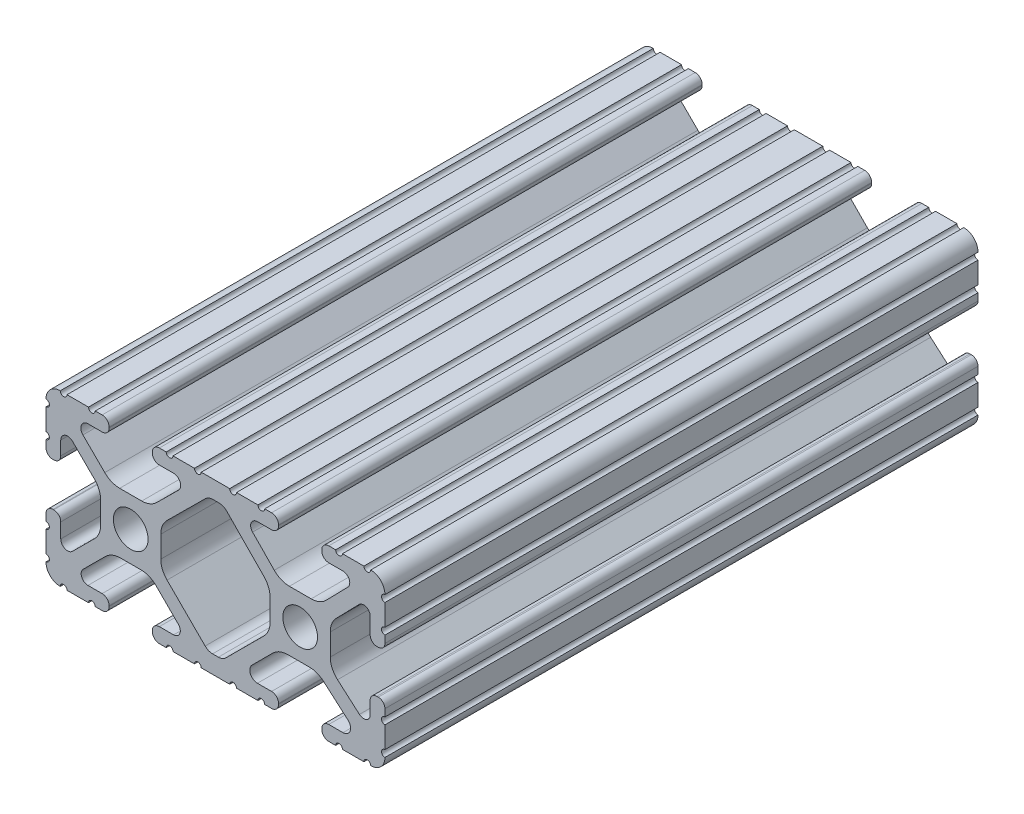
SolidWorks part; units mm, degrees
ref_plane "Front Plane" through (0, 0, 0) normal (0, 0, 1) x (1, 0, 0)
ref_plane "Top Plane" through (0, 0, 0) normal (0, 1, 0) x (1, 0, 0)
ref_plane "Right Plane" through (0, 0, 0) normal (1, 0, 0) x (0, 0, -1)
sketch "Sketch1" plane through (0, 0, 0) normal (0, 0, 1) x (1, 0, 0)
  line L0 (-7.2595, -3.8694) -> (-1.5457, -9.5728)
  line L1 (-8.1915, 1.6223) -> (-8.1915, -1.6223)
  line L2 (-1.504, 9.5765) -> (-7.252, 3.8768)
  line L3 (0.5515, 10.033) -> (-0.3952, 10.033)
  line L4 (7.2829, 3.8459) -> (1.6756, 9.5611)
  line L5 (8.1915, -1.6223) -> (8.1915, 1.6223)
  line L6 (1.5457, -9.5728) -> (7.2595, -3.8694)
  line L7 (-0.4332, -10.033) -> (0.4332, -10.033)
  line L8 (18.0171, 12.7) -> (16.9875, 12.7)
  line L9 (15.9385, 11.651) -> (15.9385, 11.5392)
  line L10 (16.9875, 10.4902) -> (19.1164, 10.4902)
  line L11 (19.8441, 8.7652) -> (16.619, 5.4551)
  line L12 (14.3449, 4.4958) -> (11.0833, 4.4958)
  line L13 (8.817, 5.4472) -> (5.5642, 8.7627)
  line L14 (6.2894, 10.4902) -> (8.4125, 10.4902)
  line L15 (9.4615, 11.5392) -> (9.4615, 11.651)
  line L16 (8.4125, 12.7) -> (7.3829, 12.7)
  line L17 (6.3669, 12.7) -> (3.1496, 12.7)
  line L18 (2.1336, 12.7) -> (-2.1336, 12.7)
  line L19 (-3.1496, 12.7) -> (-6.3669, 12.7)
  line L20 (-7.3829, 12.7) -> (-8.4125, 12.7)
  line L21 (-9.4615, 11.651) -> (-9.4615, 11.5392)
  line L22 (-8.4125, 10.4902) -> (-6.2836, 10.4902)
  line L23 (-5.5326, 8.6661) -> (-8.81, 5.4163)
  line L24 (-11.0455, 4.4958) -> (-14.3545, 4.4958)
  line L25 (-16.59, 5.4163) -> (-19.8674, 8.6661)
  line L26 (-19.1164, 10.4902) -> (-16.9875, 10.4902)
  line L27 (-15.9385, 11.5392) -> (-15.9385, 11.651)
  line L28 (-16.9875, 12.7) -> (-18.0171, 12.7)
  line L29 (-19.0331, 12.7) -> (-22.2504, 12.7)
  line L30 (-25.4, 9.5504) -> (-25.4, 6.3331)
  line L31 (-25.4, 5.3171) -> (-25.4, 4.2375)
  line L32 (-24.401, 3.2385) -> (-24.2392, 3.2385)
  line L33 (-23.1902, 4.2875) -> (-23.1902, 6.3347)
  line L34 (-21.434, 7.0665) -> (-18.148, 3.8082)
  line L35 (-17.2085, 1.5536) -> (-17.2085, -1.6952)
  line L36 (-18.1405, -3.9423) -> (-21.4316, -7.2274)
  line L37 (-23.1902, -6.498) -> (-23.1902, -4.2875)
  line L38 (-24.2392, -3.2385) -> (-24.351, -3.2385)
  line L39 (-25.4, -4.2875) -> (-25.4, -5.3171)
  line L40 (-25.4, -6.3331) -> (-25.4, -9.5504)
  line L41 (-22.2504, -12.7) -> (-19.0331, -12.7)
  line L42 (-18.0171, -12.7) -> (-16.9875, -12.7)
  line L43 (-15.9384, -11.651) -> (-15.9384, -11.5392)
  line L44 (-16.9875, -10.4902) -> (-19.1164, -10.4902)
  line L45 (-19.8341, -8.7551) -> (-16.4966, -5.4237)
  line L46 (-14.2536, -4.4958) -> (-11.1464, -4.4958)
  line L47 (-8.9034, -5.4237) -> (-5.5659, -8.7551)
  line L48 (-6.2836, -10.4902) -> (-8.4125, -10.4902)
  line L49 (-9.4616, -11.5392) -> (-9.4616, -11.651)
  line L50 (-8.4125, -12.7) -> (-7.3829, -12.7)
  line L51 (-6.3669, -12.7) -> (-3.1496, -12.7)
  line L52 (-2.1336, -12.7) -> (2.1336, -12.7)
  line L53 (3.1496, -12.7) -> (6.3669, -12.7)
  line L54 (7.3829, -12.7) -> (8.4125, -12.7)
  line L55 (9.4616, -11.651) -> (9.4616, -11.5392)
  line L56 (8.4125, -10.4902) -> (6.2894, -10.4902)
  line L57 (5.4807, -8.5353) -> (8.5979, -5.4237)
  line L58 (10.8409, -4.4958) -> (14.1026, -4.4958)
  line L59 (16.1879, -5.2766) -> (19.8682, -8.4822)
  line L60 (19.1164, -10.4902) -> (16.9875, -10.4902)
  line L61 (15.9384, -11.5392) -> (15.9384, -11.651)
  line L62 (16.9875, -12.7) -> (18.0171, -12.7)
  line L63 (19.0331, -12.7) -> (22.2504, -12.7)
  line L64 (25.4, -9.5504) -> (25.4, -6.3331)
  line L65 (25.4, -5.3171) -> (25.4, -4.2375)
  line L66 (24.401, -3.2385) -> (24.1892, -3.2385)
  line L67 (23.1902, -4.2375) -> (23.1902, -6.1559)
  line L68 (21.584, -6.8869) -> (18.2982, -4.025)
  line L69 (17.2085, -1.6308) -> (17.2085, 1.6308)
  line L70 (18.1094, 3.8465) -> (21.5263, 7.3534)
  line L71 (23.1902, 6.6769) -> (23.1902, 4.2375)
  line L72 (24.1892, 3.2385) -> (24.401, 3.2385)
  line L73 (25.4, 4.2375) -> (25.4, 5.3171)
  line L74 (25.4, 6.3332) -> (25.4, 9.5504)
  line L75 (22.2504, 12.7) -> (19.0331, 12.7)
  circle A0 centre (-12.7, 0) radius 2.6035
  circle A1 centre (12.7, 0) radius 2.6035
  arc A2 (-1.5457, -9.5728) -> (-0.4332, -10.033) centre (-0.4332, -8.4582) ccw
  arc A3 (-8.1915, -1.6223) -> (-7.2595, -3.8694) centre (-5.0165, -1.6223) ccw
  arc A4 (-7.252, 3.8768) -> (-8.1915, 1.6223) centre (-5.0165, 1.6223) ccw
  arc A5 (-0.3952, 10.033) -> (-1.504, 9.5765) centre (-0.3952, 8.4582) ccw
  arc A6 (1.6756, 9.5611) -> (0.5515, 10.033) centre (0.5515, 8.4582) ccw
  arc A7 (8.1915, 1.6223) -> (7.2829, 3.8459) centre (5.0165, 1.6223) ccw
  arc A8 (7.2595, -3.8694) -> (8.1915, -1.6223) centre (5.0165, -1.6223) ccw
  arc A9 (0.4332, -10.033) -> (1.5457, -9.5728) centre (0.4332, -8.4582) ccw
  arc A10 (18.0171, 12.7) -> (19.0331, 12.7) centre (18.5251, 12.7) ccw
  arc A11 (16.9875, 12.7) -> (15.9385, 11.651) centre (16.9875, 11.651) ccw
  arc A12 (15.9385, 11.5392) -> (16.9875, 10.4902) centre (16.9875, 11.5392) ccw
  arc A13 (19.8441, 8.7652) -> (19.1164, 10.4902) centre (19.1164, 9.4742) ccw
  arc A14 (14.3449, 4.4958) -> (16.619, 5.4551) centre (14.3449, 7.6708) ccw
  arc A15 (8.817, 5.4472) -> (11.0833, 4.4958) centre (11.0833, 7.6708) ccw
  arc A16 (6.2894, 10.4902) -> (5.5642, 8.7627) centre (6.2894, 9.4742) ccw
  arc A17 (8.4125, 10.4902) -> (9.4615, 11.5392) centre (8.4125, 11.5392) ccw
  arc A18 (9.4615, 11.651) -> (8.4125, 12.7) centre (8.4125, 11.651) ccw
  arc A19 (6.3669, 12.7) -> (7.3829, 12.7) centre (6.8749, 12.7) ccw
  arc A20 (2.1336, 12.7) -> (3.1496, 12.7) centre (2.6416, 12.7) ccw
  arc A21 (-3.1496, 12.7) -> (-2.1336, 12.7) centre (-2.6416, 12.7) ccw
  arc A22 (-7.3829, 12.7) -> (-6.3669, 12.7) centre (-6.8749, 12.7) ccw
  arc A23 (-8.4125, 12.7) -> (-9.4615, 11.651) centre (-8.4125, 11.651) ccw
  arc A24 (-9.4615, 11.5392) -> (-8.4125, 10.4902) centre (-8.4125, 11.5392) ccw
  arc A25 (-5.5326, 8.6661) -> (-6.2836, 10.4902) centre (-6.2836, 9.4235) ccw
  arc A26 (-11.0455, 4.4958) -> (-8.81, 5.4163) centre (-11.0455, 7.6708) ccw
  arc A27 (-16.59, 5.4163) -> (-14.3545, 4.4958) centre (-14.3545, 7.6708) ccw
  arc A28 (-19.1164, 10.4902) -> (-19.8674, 8.6661) centre (-19.1164, 9.4235) ccw
  arc A29 (-16.9875, 10.4902) -> (-15.9385, 11.5392) centre (-16.9875, 11.5392) ccw
  arc A30 (-15.9385, 11.651) -> (-16.9875, 12.7) centre (-16.9875, 11.651) ccw
  arc A31 (-19.0331, 12.7) -> (-18.0171, 12.7) centre (-18.5251, 12.7) ccw
  arc A32 (-23.2664, 12.6998) -> (-22.2504, 12.7) centre (-22.7584, 12.7) ccw
  arc A33 (-23.2664, 12.6998) -> (-25.3998, 10.5664) centre (-23.2918, 10.5918) ccw
  arc A34 (-25.4, 9.5504) -> (-25.3998, 10.5664) centre (-25.4, 10.0584) ccw
  arc A35 (-25.4, 5.3171) -> (-25.4, 6.3331) centre (-25.4, 5.8251) ccw
  arc A36 (-25.4, 4.2375) -> (-24.401, 3.2385) centre (-24.401, 4.2375) ccw
  arc A37 (-24.2392, 3.2385) -> (-23.1902, 4.2875) centre (-24.2392, 4.2875) ccw
  arc A38 (-21.434, 7.0665) -> (-23.1902, 6.3347) centre (-22.1596, 6.3347) ccw
  arc A39 (-17.2085, 1.5536) -> (-18.148, 3.8082) centre (-20.3835, 1.5536) ccw
  arc A40 (-18.1405, -3.9423) -> (-17.2085, -1.6952) centre (-20.3835, -1.6952) ccw
  arc A41 (-23.1902, -6.498) -> (-21.4316, -7.2274) centre (-22.1596, -6.498) ccw
  arc A42 (-23.1902, -4.2875) -> (-24.2392, -3.2385) centre (-24.2392, -4.2875) ccw
  arc A43 (-24.351, -3.2385) -> (-25.4, -4.2875) centre (-24.351, -4.2875) ccw
  arc A44 (-25.4, -6.3331) -> (-25.4, -5.3171) centre (-25.4, -5.8251) ccw
  arc A45 (-25.3998, -10.5664) -> (-25.4, -9.5504) centre (-25.4, -10.0584) ccw
  arc A46 (-25.3998, -10.5664) -> (-23.2664, -12.6998) centre (-23.2918, -10.5918) ccw
  arc A47 (-22.2504, -12.7) -> (-23.2664, -12.6998) centre (-22.7584, -12.7) ccw
  arc A48 (-18.0171, -12.7) -> (-19.0331, -12.7) centre (-18.5251, -12.7) ccw
  arc A49 (-16.9875, -12.7) -> (-15.9384, -11.651) centre (-16.9875, -11.651) ccw
  arc A50 (-15.9384, -11.5392) -> (-16.9875, -10.4902) centre (-16.9875, -11.5392) ccw
  arc A51 (-19.8341, -8.7551) -> (-19.1164, -10.4902) centre (-19.1164, -9.4742) ccw
  arc A52 (-14.2536, -4.4958) -> (-16.4966, -5.4237) centre (-14.2536, -7.6708) ccw
  arc A53 (-8.9034, -5.4237) -> (-11.1464, -4.4958) centre (-11.1464, -7.6708) ccw
  arc A54 (-6.2836, -10.4902) -> (-5.5659, -8.7551) centre (-6.2836, -9.4742) ccw
  arc A55 (-8.4125, -10.4902) -> (-9.4616, -11.5392) centre (-8.4125, -11.5392) ccw
  arc A56 (-9.4616, -11.651) -> (-8.4125, -12.7) centre (-8.4125, -11.651) ccw
  arc A57 (-6.3669, -12.7) -> (-7.3829, -12.7) centre (-6.8749, -12.7) ccw
  arc A58 (-2.1336, -12.7) -> (-3.1496, -12.7) centre (-2.6416, -12.7) ccw
  arc A59 (3.1496, -12.7) -> (2.1336, -12.7) centre (2.6416, -12.7) ccw
  arc A60 (7.3829, -12.7) -> (6.3669, -12.7) centre (6.8749, -12.7) ccw
  arc A61 (8.4125, -12.7) -> (9.4616, -11.651) centre (8.4125, -11.651) ccw
  arc A62 (9.4616, -11.5392) -> (8.4125, -10.4902) centre (8.4125, -11.5392) ccw
  arc A63 (5.4807, -8.5353) -> (6.2894, -10.4902) centre (6.2894, -9.3455) ccw
  arc A64 (10.8409, -4.4958) -> (8.5979, -5.4237) centre (10.8409, -7.6708) ccw
  arc A65 (16.1879, -5.2766) -> (14.1026, -4.4958) centre (14.1026, -7.6708) ccw
  arc A66 (19.1164, -10.4902) -> (19.8682, -8.4822) centre (19.1164, -9.3455) ccw
  arc A67 (16.9875, -10.4902) -> (15.9384, -11.5392) centre (16.9875, -11.5392) ccw
  arc A68 (15.9384, -11.651) -> (16.9875, -12.7) centre (16.9875, -11.651) ccw
  arc A69 (19.0331, -12.7) -> (18.0171, -12.7) centre (18.5251, -12.7) ccw
  arc A70 (23.2664, -12.6998) -> (22.2504, -12.7) centre (22.7584, -12.7) ccw
  arc A71 (23.2664, -12.6998) -> (25.3998, -10.5664) centre (23.2918, -10.5918) ccw
  arc A72 (25.4, -9.5504) -> (25.3998, -10.5664) centre (25.4, -10.0584) ccw
  arc A73 (25.4, -5.3171) -> (25.4, -6.3331) centre (25.4, -5.8251) ccw
  arc A74 (25.4, -4.2375) -> (24.401, -3.2385) centre (24.401, -4.2375) ccw
  arc A75 (24.1892, -3.2385) -> (23.1902, -4.2375) centre (24.1892, -4.2375) ccw
  arc A76 (21.584, -6.8869) -> (23.1902, -6.1559) centre (22.2207, -6.1559) ccw
  arc A77 (17.2085, -1.6308) -> (18.2982, -4.025) centre (20.3835, -1.6308) ccw
  arc A78 (18.1094, 3.8465) -> (17.2085, 1.6308) centre (20.3835, 1.6308) ccw
  arc A79 (23.1902, 6.6769) -> (21.5263, 7.3534) centre (22.2207, 6.6769) ccw
  arc A80 (23.1902, 4.2375) -> (24.1892, 3.2385) centre (24.1892, 4.2375) ccw
  arc A81 (24.401, 3.2385) -> (25.4, 4.2375) centre (24.401, 4.2375) ccw
  arc A82 (25.4, 6.3332) -> (25.4, 5.3171) centre (25.4, 5.8251) ccw
  arc A83 (25.3998, 10.5664) -> (25.4, 9.5504) centre (25.4, 10.0584) ccw
  arc A84 (25.3998, 10.5664) -> (23.2664, 12.6998) centre (23.2918, 10.5918) ccw
  arc A85 (22.2504, 12.7) -> (23.2664, 12.6998) centre (22.7584, 12.7) ccw
  point P248 (0, 10.033)
extrude "Boss-Extrude1" add sketch "Sketch1" along normal mid plane 88.9
